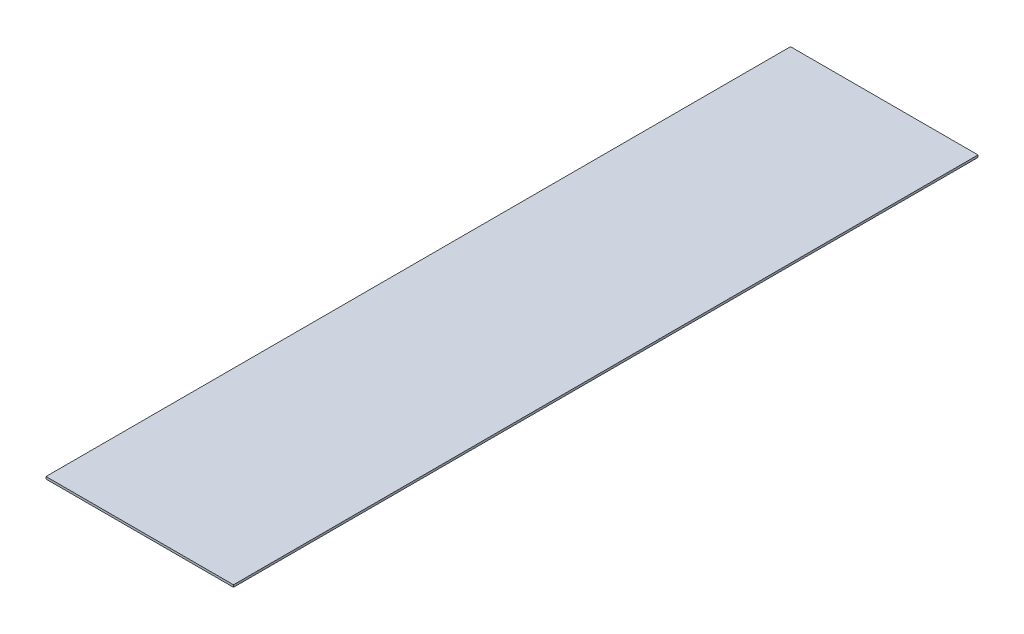
SolidWorks part; units mm, degrees
material "Oak"
ref_plane "Front Plane" through (0, 0, 0) normal (0, 0, 1) x (1, 0, 0)
ref_plane "Top Plane" through (0, 0, 0) normal (0, 1, 0) x (1, 0, 0)
ref_plane "Right Plane" through (0, 0, 0) normal (1, 0, 0) x (0, 0, -1)
sketch "Sketch1" plane through (0, 0, 0) normal (0, 1, 0) x (1, 0, 0)
  line L0 (0, 0) -> (0, 12000) construction
  line L1 (-43.171, -12.6991) -> (43.171, 12.6991)
  line L2 (-1000, 6000) -> (-700, 6000) construction
  line L7 (-43.171, -12.6991) -> (13.2696, -204.5701)
  line L8 (43.171, 12.6991) -> (99.6116, -179.1718)
  line L9 (13.2696, -204.5701) -> (99.6116, -179.1718)
  line L10 (-37.6212, -31.5658) -> (48.815, -6.488)
  line L11 (7.7198, -185.7034) -> (93.9675, -159.9847)
  line L12 (-14.9507, -108.6346) -> (71.3913, -83.2363) construction
  line L13 (20751.4706, 6000) -> (-37.6212, -31.5658) construction
  line L14 (20751.4706, 6000) -> (7.7198, -185.7034) construction
  arc A0 (0, 0) -> (0, 12000) centre (20751.4706, 6000) cw
  point P1 (0, 0)
  point P4 (0, 12000)
  point P5 (0, 0)
  point P6 (0, 6000)
  point P7 (-700, 6000)
  point P8 (-1000, 6000)
  point P12 (-850, 6000)
  dimension "D8" = 12159.9166
  dimension "D1" = 12000
  dimension "D2" = 1000
  dimension "D3" = 700
  dimension "D4" = 200
  dimension "D5" = 90
  dimension "D6" = 160
  dimension "D7" = 160.668
  dimension "D9" = 16.392
sketch "Sketch2" plane through (0, 0, 0) normal (0, 1, 0) x (1, 0, 0)
  line L1 (-2097.06, -2727.5223) -> (2097.06, -2727.5223)
  line L2 (-2097.06, -2727.5223) -> (-2097.06, 13927.3312)
  line L3 (-2097.06, 13927.3312) -> (2097.06, 13927.3312)
  line L4 (2097.06, -2727.5223) -> (2097.06, 13927.3312)
  line L5 (0, 5570.299) -> (0, 55570.299) construction
extrude "Boss-Extrude1" add sketch "Sketch2" against normal blind 50
